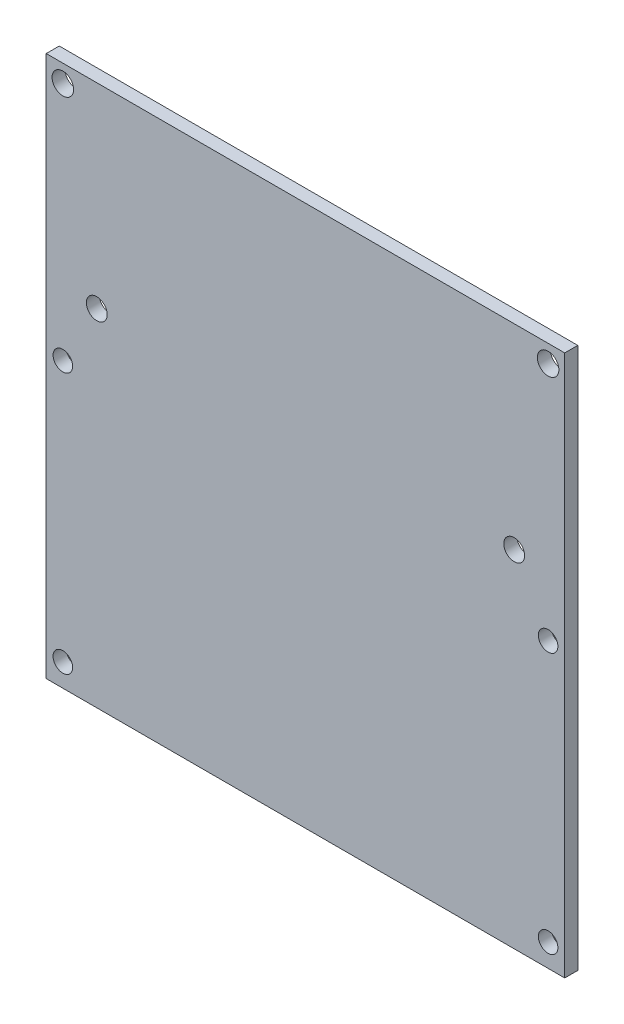
SolidWorks part; units mm, degrees
ref_plane "前视基准面" through (0, 0, 0) normal (0, 0, 1) x (1, 0, 0)
ref_plane "上视基准面" through (0, 0, 0) normal (0, 1, 0) x (1, 0, 0)
ref_plane "右视基准面" through (0, 0, 0) normal (1, 0, 0) x (0, 0, -1)
other "Configuration Table"
sketch "草图1" plane through (0, 0, 0) normal (0, 0, 1) x (1, 0, 0)
  line L0 (0, 0) -> (0, -83)
  line L1 (0, 0) -> (79.5, 0)
  line L2 (79.5, 0) -> (79.5, -83)
  line L3 (79.5, -83) -> (0, -83)
  dimension "D1" = 83
  dimension "D2" = 79.5
extrude "凸台-拉伸1" add sketch "草图1" along normal blind 2
sketch "草图2" plane through (0, 0, 2) normal (0, 0, 1) x (1, 0, 0)
  line L0 (0, -83) -> (2.55, -83) construction
  line L1 (0, -83) -> (79.5, -83) construction
  line L2 (0, -83) -> (0, -81) construction
  line L3 (0, 0) -> (0, -83) construction
  line L4 (0, -81) -> (0, -79.5) construction
  line L5 (2.55, -79.5) -> (2.55, -39.5) construction
  line L6 (76.95, -39.5) -> (76.95, -79.5) construction
  line L7 (79.5, 0) -> (0, 0) construction
  line L8 (39.75, -83) -> (39.75, 1.5078) construction
  circle A0 centre (2.55, -79.5) radius 1.5
  circle A1 centre (2.55, -39.5) radius 1.5
  circle A2 centre (76.95, -39.5) radius 1.5
  circle A3 centre (76.95, -79.5) radius 1.5
  circle A4 centre (2.55, -2.7) radius 1.65
  circle A5 centre (76.95, -2.7) radius 1.65
  dimension "D1" = 2.7
  dimension "D2" = 3.3
  dimension "D3" = 2.55
extrude "切除-拉伸1" cut sketch "草图2" against normal blind 3
sketch "草图3" plane through (0, 0, 0) normal (0, 0, 1) x (1, 0, 0)
  line L0 (39.75, -83) -> (39.75, -50083) construction
  line L1 (0, -83) -> (79.5, -83) construction
  line L3 (79.5, 0) -> (0, 0) construction
  circle A0 centre (7.75, -30) radius 1.6
  circle A2 centre (71.75, -30) radius 1.6
  point P4 (39.75, -83)
  point P7 (0, 0)
  point P10 (9.073, -39.2932)
  point P15 (12.8017, -60.1479)
  dimension "D2" = 3.2
  dimension "D1" = 30
  dimension "D3" = 32
extrude "切除-拉伸2" cut sketch "草图3" along normal up to next
